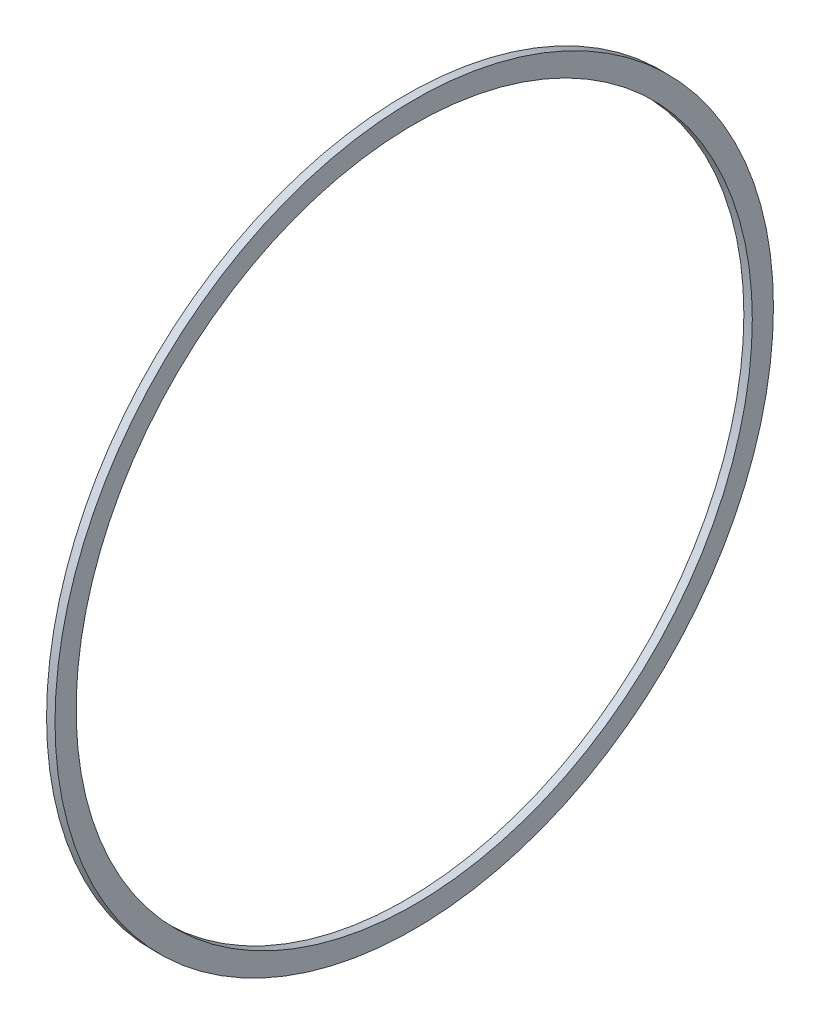
SolidWorks part; units mm, degrees
material "201 Annealed Stainless Steel (SS)"
ref_plane "Front Plane" through (0, 0, 0) normal (0, 0, 1) x (1, 0, 0)
ref_plane "Top Plane" through (0, 0, 0) normal (0, 1, 0) x (1, 0, 0)
ref_plane "Right Plane" through (0, 0, 0) normal (1, 0, 0) x (0, 0, -1)
sketch "Sketch1" plane through (0, 0, 0) normal (1, 0, 0) x (0, 0, -1)
  circle A2 centre (0, 0) radius 42.5
  circle A3 centre (0, 0) radius 40
  dimension "D1" = 85
  dimension "D2" = 80
extrude "Boss-Extrude1" add sketch "Sketch1" along normal blind 1
